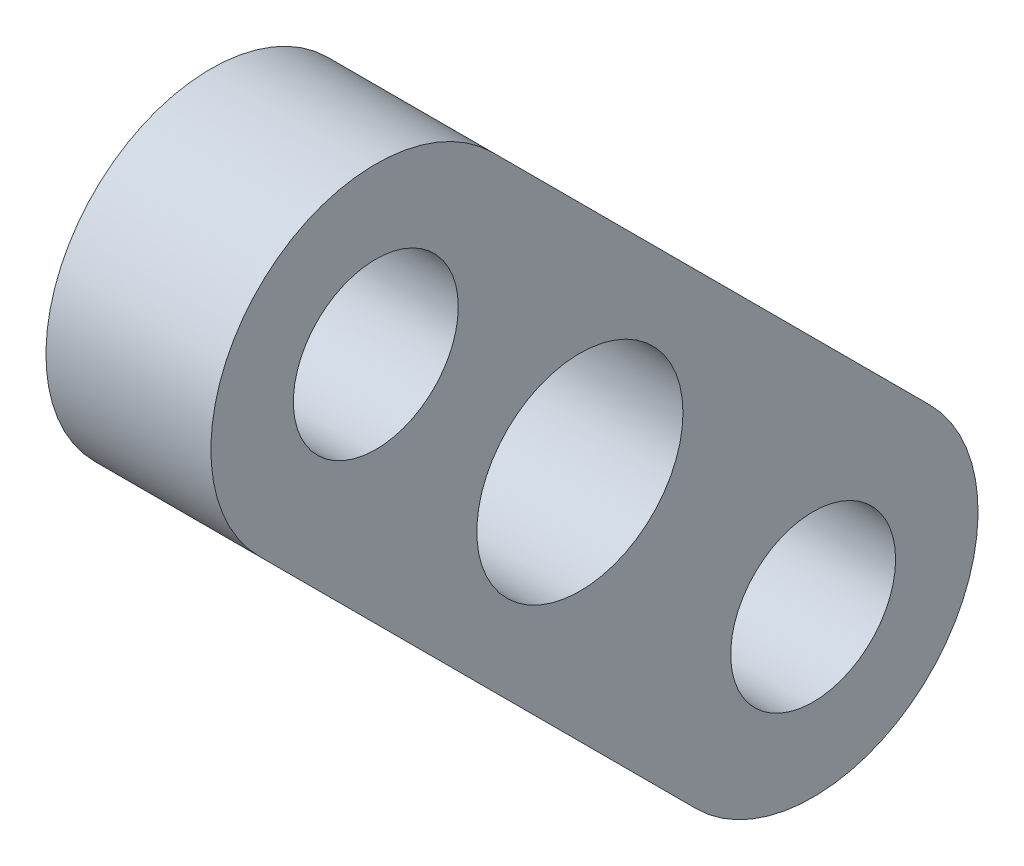
SolidWorks part; units mm, degrees
ref_plane "Front Plane" through (0, 0, 0) normal (0, 0, 1) x (1, 0, 0)
ref_plane "Top Plane" through (0, 0, 0) normal (0, 1, 0) x (1, 0, 0)
ref_plane "Right Plane" through (0, 0, 0) normal (1, 0, 0) x (0, 0, -1)
sketch "Sketch1" plane through (0, 0, 0) normal (1, 0, 0) x (0, 0, -1)
  line L0 (0, 0) -> (0, 14.3103) construction
  line L1 (-10.1168, 10.1168) -> (10.1168, -10.1168) construction
  line L2 (-3.8891, 1.0607) -> (1.4142, -4.2426)
  line L3 (-1.0607, 3.8891) -> (4.2426, -1.4142)
  circle A0 centre (0, 0) radius 4 construction
  circle A1 centre (-2.4749, 2.4749) radius 1
  circle A2 centre (2.8284, -2.8284) radius 1
  arc A3 (-1.0356, 3.8636) -> (-3.8636, 1.0356) centre (-2.4749, 2.4749) ccw
  arc A4 (1.1056, -3.8442) -> (3.8442, -1.1056) centre (2.8284, -2.8284) ccw
  circle A5 centre (0, 0) radius 1.25
  circle A6 centre (0, 0) radius 3.5 construction
  point P7 (0, 0)
  point P20 (0, 0)
  dimension "D2" = 8
  dimension "D3" = 2
  dimension "D4" = 2
  dimension "D5" = 4
  dimension "D6" = 4
  dimension "D7" = 2.5
  dimension "D8" = 7
  dimension "D1" = 45
extrude "Boss-Extrude1" add sketch "Sketch1" along normal blind 2
